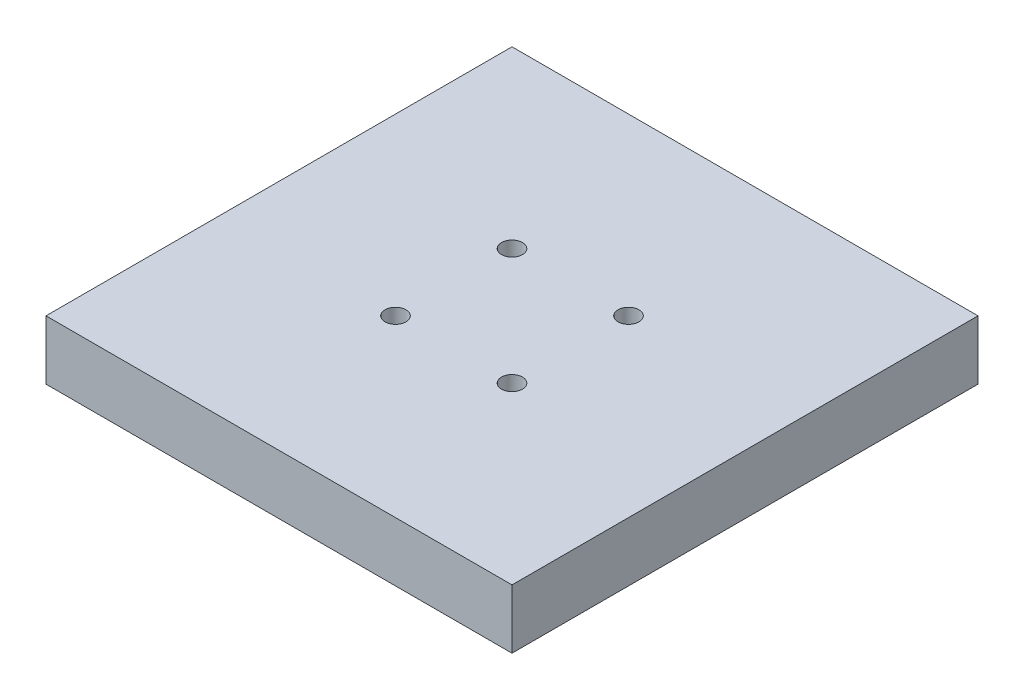
SolidWorks part; units mm, degrees
material "Aleación 1060"
ref_plane "Alzado" through (0, 0, 0) normal (0, 0, 1) x (1, 0, 0)
ref_plane "Planta" through (0, 0, 0) normal (0, 1, 0) x (1, 0, 0)
ref_plane "Vista lateral" through (0, 0, 0) normal (1, 0, 0) x (0, 0, -1)
sketch "Croquis1" plane through (0, 0, 0) normal (0, 1, 0) x (1, 0, 0)
  line L1 (50, -50) -> (-50, -50)
  line L2 (50, -50) -> (50, 50)
  line L3 (50, 50) -> (-50, 50)
  line L4 (-50, -50) -> (-50, 50)
  line L5 (50, -50) -> (-50, 50) construction
  line L6 (50, 50) -> (-50, -50) construction
  point P0 (0, 0)
  dimension "D1" = 100
extrude "Saliente-Extruir1" add sketch "Croquis1" along normal blind 12.7
sketch "Croquis3" plane through (0, 0, 0) normal (0, -1, 0) x (1, 0, 0)
  line L4 (-50, 50) -> (-50, -50)
  line L5 (-50, -50) -> (50, -50)
  line L6 (50, -50) -> (50, 50)
  line L7 (50, 50) -> (-50, 50)
  line L8 (-50, 50) -> (-50, -50)
  line L9 (-50, -50) -> (50, -50)
  line L10 (50, -50) -> (50, 50)
  line L11 (50, 50) -> (-50, 50)
  circle A0 centre (-12.5, -12.5) radius 2.25 construction
  circle A1 centre (12.5, -12.5) radius 2.25 construction
  circle A2 centre (-12.5, 12.5) radius 2.25 construction
  circle A3 centre (12.5, 12.5) radius 2.25 construction
  circle A4 centre (-12.5, -12.5) radius 2.25
  circle A5 centre (12.5, -12.5) radius 2.25
  circle A6 centre (-12.5, 12.5) radius 2.25
  circle A7 centre (12.5, 12.5) radius 2.25
  dimension "D1" = 0
extrude "Cortar-Extruir1" cut sketch "Croquis3" against normal through all flip side to cut
